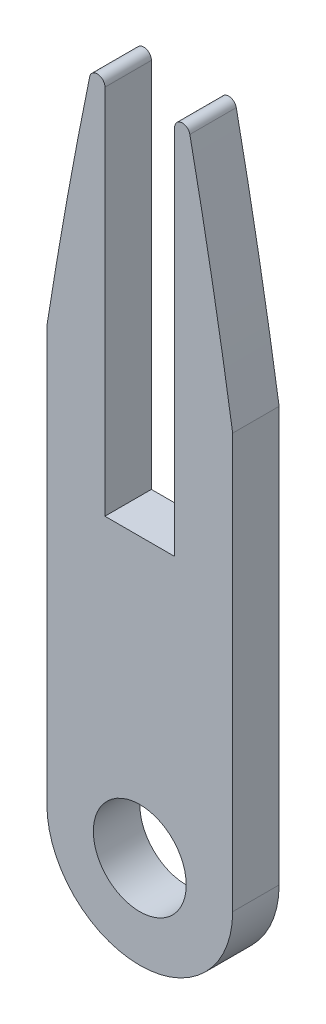
SolidWorks part; units mm, degrees
ref_plane "Front Plane" through (0, 0, 0) normal (0, 0, 1) x (1, 0, 0)
ref_plane "Top Plane" through (0, 0, 0) normal (0, 1, 0) x (1, 0, 0)
ref_plane "Right Plane" through (0, 0, 0) normal (1, 0, 0) x (0, 0, -1)
sketch "Sketch1" plane through (0, 0, 0) normal (0, 0, 1) x (1, 0, 0)
  line L0 (0, 0) -> (0, 113.3398) construction
  line L1 (-9.525, 177.8) -> (9.525, 177.8) construction
  line L2 (-9.525, 177.8) -> (-9.525, 76.2)
  line L3 (-9.525, 76.2) -> (9.525, 76.2)
  line L4 (9.525, 177.8) -> (9.525, 76.2)
  line L5 (-25.4, 0) -> (-25.4, 113.3398)
  line L6 (25.4, 0) -> (25.4, 113.3398)
  circle A0 centre (0, 0) radius 12.7
  arc A2 (-9.525, 177.8) -> (-13.6916, 178.2236) centre (-11.6298, 177.8) ccw
  arc A3 (-13.6916, 178.2236) -> (-25.4, 113.3398) centre (1327.3575, -97.2692) ccw
  arc A4 (9.525, 177.8) -> (13.6916, 178.2236) centre (11.6298, 177.8) cw
  arc A5 (13.6916, 178.2236) -> (25.4, 113.3398) centre (-1327.3575, -97.2692) cw
  arc A6 (-25.4, 0) -> (25.4, 0) centre (0, 0) ccw
  arc A7 (25.4, 113.3398) -> (-25.4, 113.3398) centre (0, 113.3398) ccw
  point P3 (0, 56.6699)
  point P9 (0, 76.2)
  dimension "D1" = 25.4
  dimension "D2" = 76.2
  dimension "D5" = 1369.054
  dimension "D6" = 2.1048
  dimension "D3" = 50.8
  dimension "D4" = 19.05
  dimension "D7" = 101.6
  dimension "D8" = 113.3398
extrude "Boss-Extrude1" add sketch "Sketch1" along normal mid plane 12.7 contours A5 A7 L4 L3 L2 A3 L5 A6 L6 A0 | A7 A5 A4 L4 | A7 L2 A2 A3
